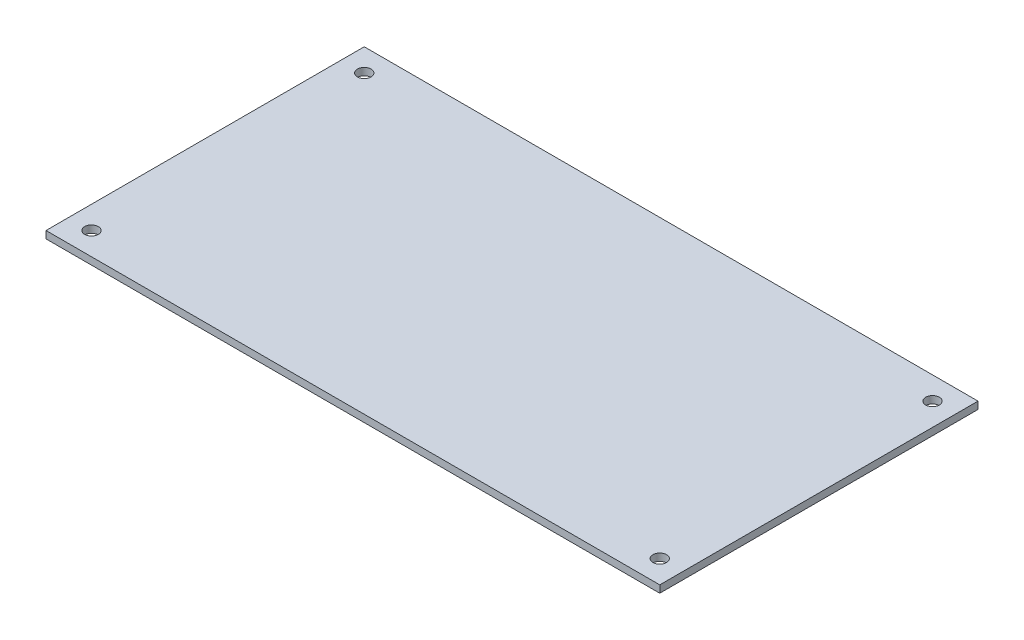
SolidWorks part; units mm, degrees
ref_plane "Front" through (0, 0, 0) normal (0, 0, 1) x (1, 0, 0)
ref_plane "Top" through (0, 0, 0) normal (0, 1, 0) x (1, 0, 0)
ref_plane "Right" through (0, 0, 0) normal (1, 0, 0) x (0, 0, -1)
sketch "Sketch1" plane through (0, 0, 0) normal (0, 1, 0) x (1, 0, 0)
  line L1 (-67.5, -35) -> (67.5, -35)
  line L2 (-67.5, -35) -> (-67.5, 35)
  line L3 (-67.5, 35) -> (67.5, 35)
  line L4 (67.5, -35) -> (67.5, 35)
  line L5 (-67.5, -35) -> (67.5, 35) construction
  line L6 (-67.5, 35) -> (67.5, -35) construction
  point P0 (0, 0)
  dimension "D1" = 135
  dimension "D2" = 70
extrude "Boss-Extrude1" add sketch "Sketch1" along normal blind 1.6
sketch "Sketch2" plane through (0, 1.6, 0) normal (0, 1, 0) x (1, 0, 0)
  line L0 (-67.5, 35) -> (-67.5, -35) construction
  line L1 (67.5, 35) -> (-67.5, 35) construction
  line L2 (0, 35) -> (0, -35) construction
  line L3 (-67.5, -35) -> (67.5, -35) construction
  line L4 (-67.5, 0) -> (67.5, 0) construction
  line L5 (67.5, -35) -> (67.5, 35) construction
  circle A0 centre (-62.5, 30) radius 1.5
  circle A1 centre (62.5, 30) radius 1.5
  circle A2 centre (62.5, -30) radius 1.5
  circle A3 centre (-62.5, -30) radius 1.5
  dimension "D1" = 3
  dimension "D2" = 5
  dimension "D3" = 5
extrude "Cut-Extrude1" cut sketch "Sketch2" against normal up to next and the other way through all
